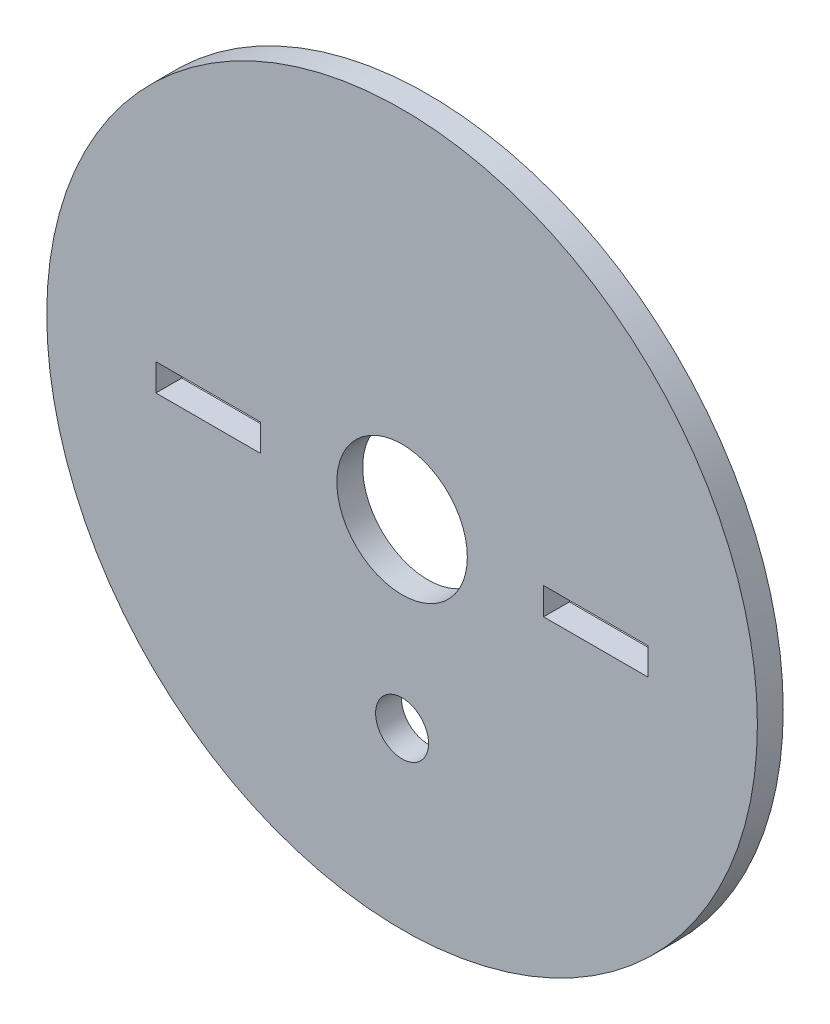
SolidWorks part; units mm, degrees
ref_plane "前视基准面" through (0, 0, 0) normal (0, 0, 1) x (1, 0, 0)
ref_plane "上视基准面" through (0, 0, 0) normal (0, 1, 0) x (1, 0, 0)
ref_plane "右视基准面" through (0, 0, 0) normal (1, 0, 0) x (0, 0, -1)
sketch "草图1" plane through (0, 0, 0) normal (0, 0, 1) x (1, 0, 0)
  line L0 (0, 0) -> (0, 14) construction
  line L1 (0, 14) -> (-15, 14) construction
  line L2 (0, 7) -> (-3.9018, 7) construction
  line L3 (-19.05, 15.05) -> (-10.95, 15.05)
  line L4 (-19.05, 15.05) -> (-19.05, 12.95)
  line L5 (-19.05, 12.95) -> (-10.95, 12.95)
  line L6 (-10.95, 15.05) -> (-10.95, 12.95)
  line L7 (-19.05, 15.05) -> (-10.95, 12.95) construction
  line L8 (-19.05, 12.95) -> (-10.95, 15.05) construction
  line L13 (10.95, 15.05) -> (10.95, 12.95)
  line L14 (19.05, 15.05) -> (10.95, 15.05)
  line L15 (19.05, 15.05) -> (19.05, 12.95)
  line L16 (19.05, 12.95) -> (10.95, 12.95)
  circle A0 centre (0, 0) radius 2.05
  circle A1 centre (0, 14) radius 2.05 construction
  circle A2 centre (0, 14) radius 5.05
  circle A4 centre (0, 14) radius 12 construction
  circle A9 centre (0, 14) radius 27.5
  circle A10 centre (0, 14) radius 3.35 construction
  dimension "D1" = 4.1
  dimension "D3" = 4.1
  dimension "D7" = 10.1
  dimension "D9" = 24
  dimension "D11" = 6.7
  dimension "D12" = 55
  dimension "D2" = 14
  dimension "D4" = 15
  dimension "D5" = 8.1
  dimension "D6" = 2.1
  dimension "D8" = 0
extrude "凸台-拉伸1" add sketch "草图1" along normal blind 2
